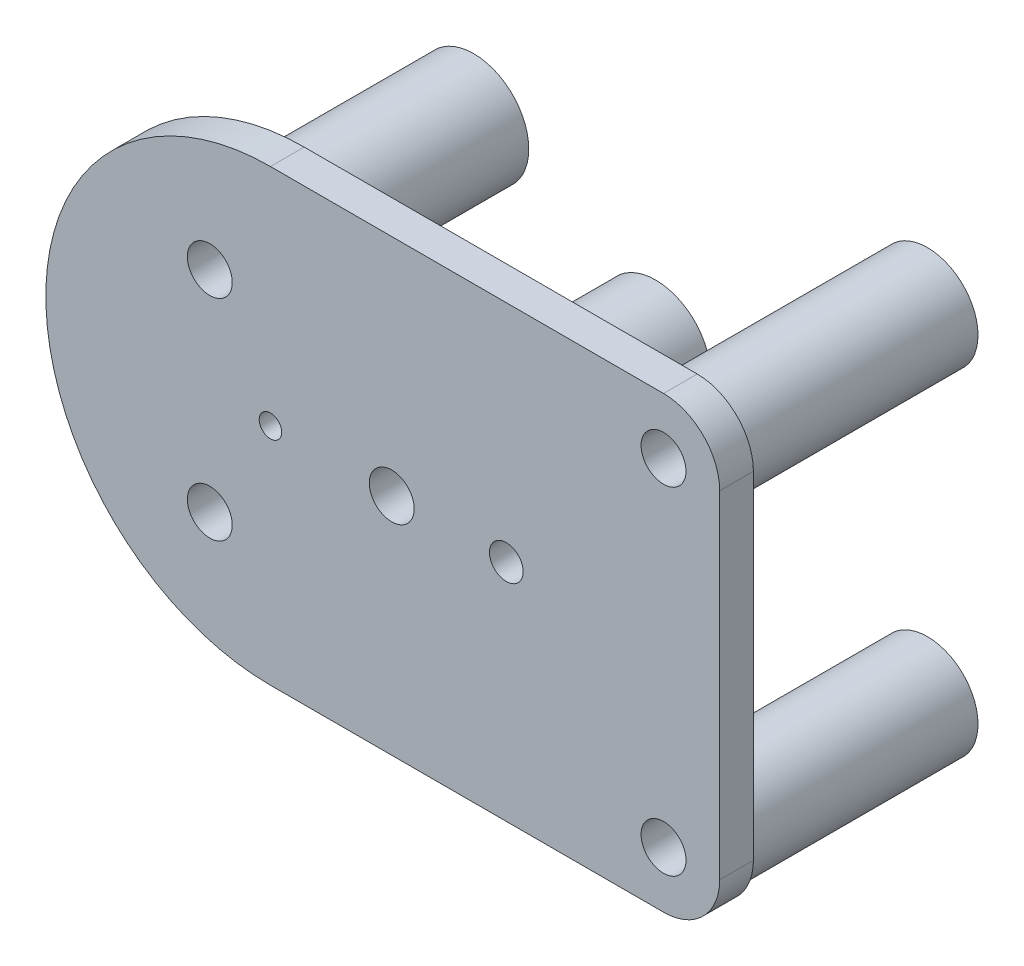
SolidWorks part; units mm, degrees
ref_plane "Ebene vorne" through (0, 0, 0) normal (0, 0, 1) x (1, 0, 0)
ref_plane "Ebene oben" through (0, 0, 0) normal (0, 1, 0) x (1, 0, 0)
ref_plane "Ebene rechts" through (0, 0, 0) normal (1, 0, 0) x (0, 0, -1)
sketch "Skizze1" plane through (0, 0, 0) normal (0, 0, 1) x (1, 0, 0)
  line L0 (0, 20) -> (40, 20)
  line L1 (0, -20) -> (40, -20)
  line L2 (40, 20) -> (40, -20)
  line L3 (0, 0) -> (40, 0) construction
  circle A0 centre (0, 0) radius 20
  circle A1 centre (0, 0) radius 1
  circle A2 centre (21, 0) radius 1.5
  circle A3 centre (35, 15) radius 2
  circle A4 centre (35, -15) radius 2
  dimension "D1" = 40
  dimension "D2" = 2
  dimension "D4" = 3
  dimension "D6" = 4
  dimension "D3" = 40
  dimension "D5" = 21
  dimension "D7" = 5
  dimension "D8" = 5
extrude "Aufsatz-Linear austragen1" add sketch "Skizze1" along normal blind 3
sketch "Skizze2" plane through (0, 0, 0) normal (0, 0, -1) x (-1, 0, 0)
  line L0 (0, 0) -> (-10.8, 0) construction
  line L1 (0, 0) -> (0, 5) construction
  circle A0 centre (-10.8, 0) radius 4.9
  circle A2 centre (5.4, 9.3531) radius 4.9
  circle A3 centre (5.4, -9.3531) radius 4.9
  point P11 (0, 0)
  dimension "D1" = 9.8
  dimension "D2" = 10.8
  dimension "D3" = 5
  dimension "D5" = 10.8
  dimension "D6" = 10.8
  dimension "D4" = 3
extrude "Aufsatz-Linear austragen2" add sketch "Skizze2" along normal blind 20.5
sketch "Skizze3" plane through (0, 0, -20.5) normal (0, 0, -1) x (-1, 0, 0)
  circle A0 centre (-10.8, 0) radius 2
  circle A3 centre (5.4, 9.3531) radius 2
  circle A4 centre (5.4, -9.3531) radius 2
  point P9 (0.35, 0.2021)
  point P10 (0, 0)
  dimension "D1" = 4
  dimension "D2" = 3
extrude "Schnitt-Linear austragen1" cut sketch "Skizze3" against normal through all
fillet "Verrundung1" radius 5 2 edges at (40, -20, 1.5) (40, 20, 1.5)
sketch "Skizze4" plane through (0, 0, 0) normal (0, 0, -1) x (-1, 0, 0)
  circle A0 centre (-35, 15) radius 2
  circle A1 centre (-35, 15) radius 4.5
  circle A2 centre (-35, -15) radius 2
  circle A3 centre (-35, -15) radius 4.5
  dimension "D1" = 4
  dimension "D2" = 9
  dimension "D3" = 9
  dimension "D4" = 4
extrude "Aufsatz-Linear austragen3" add sketch "Skizze4" along normal up to surface (20.5 mm away) up to face at (8.8, 0, -20.5)
